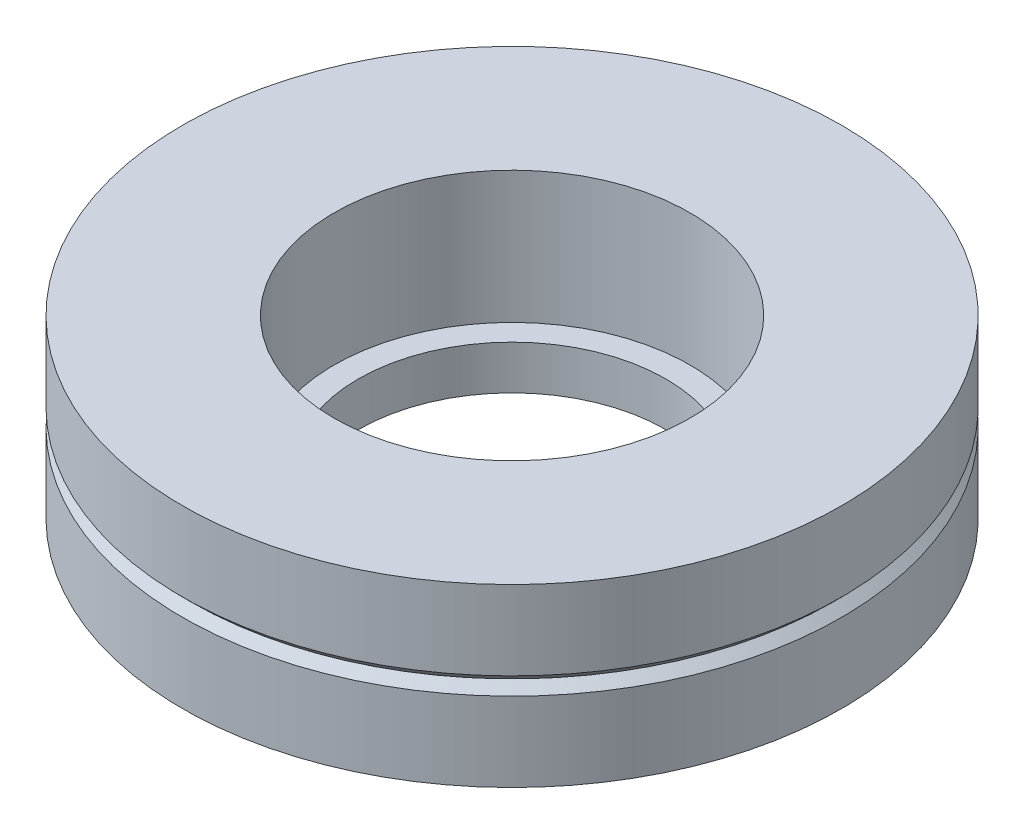
SolidWorks part; units mm, degrees
ref_plane "Front Plane" through (0, 0, 0) normal (0, 0, 1) x (1, 0, 0)
ref_plane "Top Plane" through (0, 0, 0) normal (0, 1, 0) x (1, 0, 0)
ref_plane "Right Plane" through (0, 0, 0) normal (1, 0, 0) x (0, 0, -1)
sketch "Sketch1" plane through (0, 0, 0) normal (0, 0, 1) x (1, 0, 0)
  line L0 (0, 0) -> (0, 13.3528) construction
  line L1 (2.5, 8) -> (15, 8)
  line L2 (15, 8) -> (15, 4.4)
  line L3 (15, 4.4) -> (14.6, 4)
  line L4 (14.6, 4) -> (15, 3.6)
  line L5 (15, 3.6) -> (15, 0)
  line L6 (15, 0) -> (2.5, 0)
  line L7 (14.6, 4) -> (14.6, 0) construction
  line L8 (14.6, 4) -> (14.6, 8) construction
  line L9 (2.5, 8) -> (2.5, 0)
  dimension "D1" = 30
  dimension "D2" = 5
  dimension "D3" = 0.4
  dimension "D4" = 8
revolve "Revolve1" add sketch "Sketch1" angle 360 about L0
sketch "Sketch2" plane through (0, 8, 0) normal (0, 1, 0) x (1, 0, 0)
  circle A0 centre (0, 0) radius 8.1
  dimension "D1" = 16.2
extrude "Cut-Extrude1" cut sketch "Sketch2" against normal blind 6
sketch "Sketch3" plane through (0, 2, 0) normal (0, 1, 0) x (1, 0, 0)
  circle A0 centre (0, 0) radius 7
  dimension "D1" = 14
extrude "Cut-Extrude2" cut sketch "Sketch3" against normal blind 6
